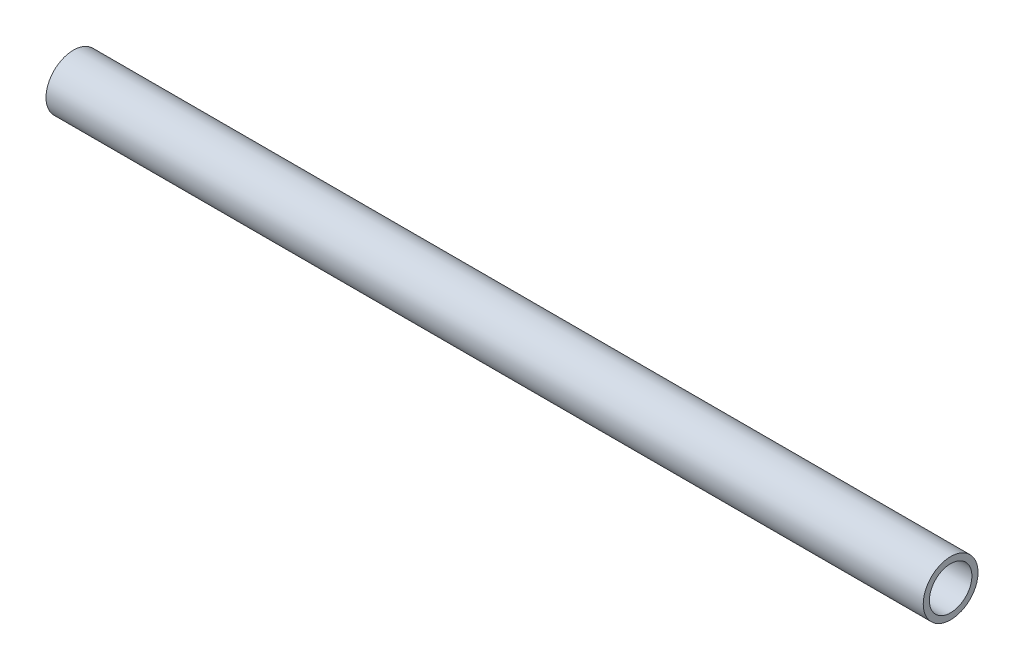
SolidWorks part; units mm, degrees
ref_plane "Front Plane" through (0, 0, 0) normal (0, 0, 1) x (1, 0, 0)
ref_plane "Top Plane" through (0, 0, 0) normal (0, 1, 0) x (1, 0, 0)
ref_plane "Right Plane" through (0, 0, 0) normal (1, 0, 0) x (0, 0, -1)
sketch "Sketch1" plane through (0, 0, 0) normal (0, 0, 1) x (1, 0, 0)
  line L0 (50.8, 2.4638) -> (50.8, -2.4638) construction
  line L1 (-50.8, 3.175) -> (50.8, 3.175) construction
  line L2 (-50.8, 3.175) -> (-50.8, 2.4638) construction
  line L3 (-50.8, 2.4638) -> (50.8, 2.4638) construction
  line L4 (50.8, 3.175) -> (50.8, 2.4638) construction
  line L5 (-50.8, -2.4638) -> (50.8, -2.4638) construction
  line L6 (-50.8, -2.4638) -> (-50.8, -3.175) construction
  line L7 (-50.8, -3.175) -> (50.8, -3.175) construction
  line L8 (50.8, -2.4638) -> (50.8, -3.175) construction
  line L9 (-50.8, 2.4638) -> (-50.8, -2.4638) construction
  line L10 (-50.8, 0) -> (50.8, 0) construction
  point P10 (-41.275, 0)
  point P12 (41.275, 0)
  dimension "OD" = 6.35
  dimension "ID" = 4.9276
  dimension "Wall Thickness" = 0.7112
  dimension "Length" = 101.6
  dimension "D5" = 9.525
  dimension "D6" = 9.525
sketch "Sketch2" plane through (0, 0, 0) normal (1, 0, 0) x (0, 0, -1)
  line L0 (0, 2.4638) -> (0, -2.4638) construction
  line L1 (-3.175, 0) -> (-2.4638, 0) construction
  line L2 (2.4638, 0) -> (3.175, 0) construction
  circle A0 centre (0, 0) radius 3.175 construction
  circle A1 centre (0, 0) radius 2.4638 construction
  dimension "OD" = 6.35
  dimension "ID" = 4.9276
sketch "Sketch3" plane through (0, 0, 0) normal (0, 0, 1) x (1, 0, 0)
  line L1 (-50.8, 3.175) -> (50.8, 3.175)
  line L2 (-50.8, 3.175) -> (-50.8, 2.4638)
  line L3 (-50.8, 2.4638) -> (50.8, 2.4638)
  line L4 (50.8, 3.175) -> (50.8, 2.4638)
revolve "Revolve1" add sketch "Sketch3" angle 360 about L10
equation "\"D5@Sketch1\" = \"OD@Sketch1\" * 1.5"
equation "\"D6@Sketch1\" = \"OD@Sketch1\" * 1.5"
